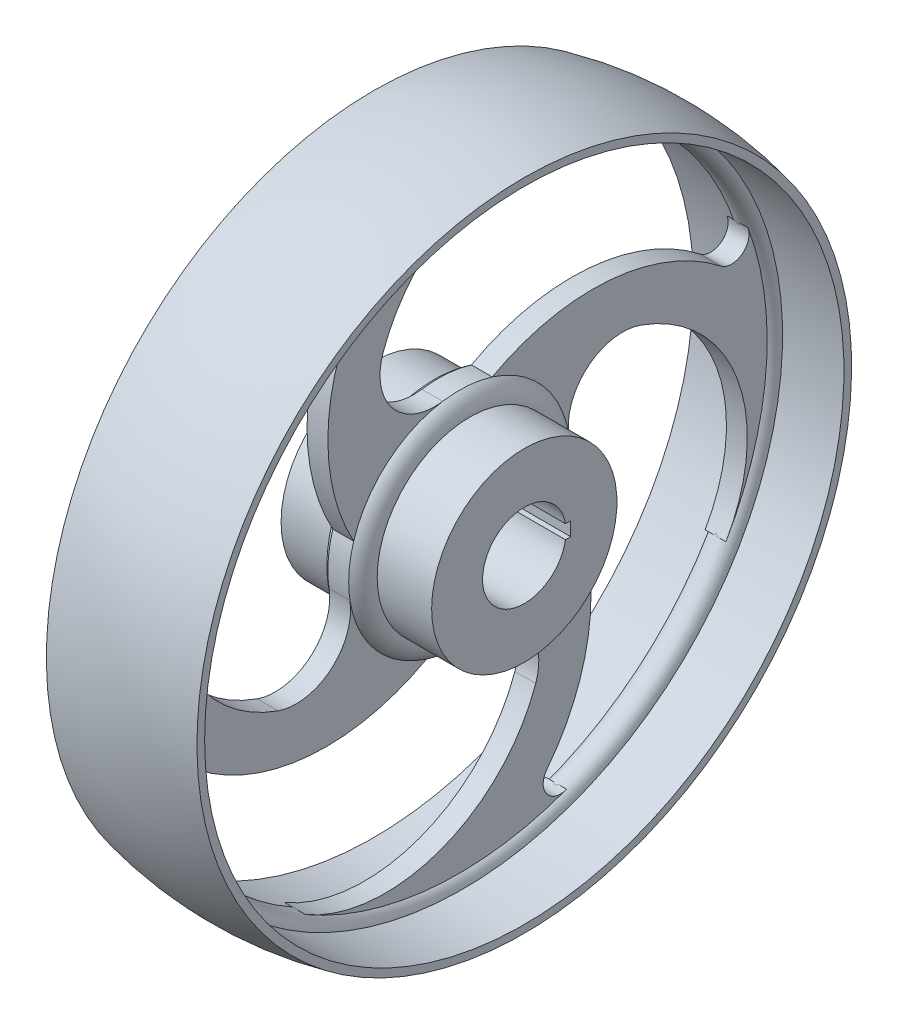
SolidWorks part; units mm, degrees
ref_plane "Front Plane" through (0, 0, 0) normal (0, 0, 1) x (1, 0, 0)
ref_plane "Top Plane" through (0, 0, 0) normal (0, 1, 0) x (1, 0, 0)
ref_plane "Right Plane" through (0, 0, 0) normal (1, 0, 0) x (0, 0, -1)
sketch "Sketch1" plane through (0, 0, 0) normal (0, 0, 1) x (1, 0, 0)
  line L0 (-32.5, 40) -> (-9, 40)
  line L1 (32.5, 18) -> (32.5, 40)
  line L2 (-32.5, 18) -> (-32.5, 40)
  line L3 (-145, 0) -> (145, 0) construction
  line L5 (-32.5, 138) -> (-32.5, 141.3108)
  line L7 (-32.5, 138) -> (-6, 138)
  line L8 (6, 138) -> (32.5, 138)
  line L9 (-145, 40) -> (145, 40) construction
  line L10 (32.5, 138) -> (32.5, 141.3108)
  line L11 (-32.5, 18) -> (32.5, 18)
  line L12 (9, 40) -> (32.5, 40)
  line L13 (-145, 18) -> (145, 18) construction
  arc A1 (32.5, 141.3108) -> (-32.5, 141.3108) centre (0, 0) ccw
  arc A3 (-6, 138) -> (6, 138) centre (0, 138.9286) ccw
  arc A6 (9, 40) -> (-9, 40) centre (0, 40) ccw
  point P3 (32.5, 0)
  point P5 (32.5, 145)
  point P6 (-32.5, 0)
  point P7 (-32.5, 145)
  point P12 (290.3079, 25.6106)
  point P13 (580.3079, 25.6106)
  point P18 (-145, 50)
  point P19 (145, 50)
  dimension "D1" = 138
  dimension "D5" = 6.0714
  dimension "D4" = 145
  dimension "D7" = 18
  dimension "D6" = 40
  dimension "D2" = 65
  dimension "D3" = 32.5
  dimension "D8" = 18
revolve "Revolve1" add sketch "Sketch1" angle 360 about L3
sketch "Sketch7" plane through (0, 0, 0) normal (1, 0, 0) x (0, 0, -1)
  circle A0 centre (0, 0) radius 132.8571
extrude "Boss-Extrude2" add sketch "Sketch7" against normal mid plane 9
sketch "Sketch8" plane through (0, 0, 0) normal (1, 0, 0) x (0, 0, -1)
  circle A0 centre (0, 0) radius 132.8571 construction
  arc A2 (14.1614, 45.648) -> (-7.213, 47.2468) centre (0, 0) ccw
  arc A4 (66.4286, 115.0577) -> (-32.9427, 78.3112) centre (32, 55.4256) ccw
  arc A5 (-32.9427, 78.3112) -> (-7.213, 47.2468) centre (-10.7622, 70.4949) ccw
  circle A6 centre (0, 0) radius 47.7942 construction
  arc A7 (112.8975, 37.7385) -> (14.1614, 45.648) centre (57.5288, -33.2143) ccw
  arc A8 (112.8975, 37.7385) -> (124.5422, 46.2629) centre (117.5116, 43.6513) ccw
  arc A9 (124.5422, 46.2629) -> (66.4286, 115.0577) centre (0, 0) ccw
  arc A10 (127.0519, 38.8437) -> (66.4286, 115.0577) centre (0, 0) ccw
  arc A11 (115.0577, -66.4286) -> (78.3112, 32.9427) centre (55.4256, -32) ccw
  arc A12 (46.2629, -124.5422) -> (115.0577, -66.4286) centre (0, 0) ccw
  arc A13 (37.7385, -112.8975) -> (46.2629, -124.5422) centre (43.6513, -117.5116) ccw
  arc A14 (37.7385, -112.8975) -> (45.648, -14.1614) centre (-33.2143, -57.5288) ccw
  arc A15 (45.648, -14.1614) -> (47.2468, 7.213) centre (0, 0) ccw
  arc A16 (78.3112, 32.9427) -> (47.2468, 7.213) centre (70.4949, 10.7622) ccw
  arc A17 (-66.4286, -115.0577) -> (32.9427, -78.3112) centre (-32, -55.4256) ccw
  arc A18 (-124.5422, -46.2629) -> (-66.4286, -115.0577) centre (0, 0) ccw
  arc A19 (-112.8975, -37.7385) -> (-124.5422, -46.2629) centre (-117.5116, -43.6513) ccw
  arc A20 (-112.8975, -37.7385) -> (-14.1614, -45.648) centre (-57.5288, 33.2143) ccw
  arc A21 (-14.1614, -45.648) -> (7.213, -47.2468) centre (0, 0) ccw
  arc A22 (32.9427, -78.3112) -> (7.213, -47.2468) centre (10.7622, -70.4949) ccw
  arc A23 (-115.0577, 66.4286) -> (-78.3112, -32.9427) centre (-55.4256, 32) ccw
  arc A24 (-46.2629, 124.5422) -> (-115.0577, 66.4286) centre (0, 0) ccw
  arc A25 (-37.7385, 112.8975) -> (-46.2629, 124.5422) centre (-43.6513, 117.5116) ccw
  arc A26 (-37.7385, 112.8975) -> (-45.648, 14.1614) centre (33.2143, 57.5288) ccw
  arc A27 (-45.648, 14.1614) -> (-47.2468, -7.213) centre (0, 0) ccw
  arc A28 (-78.3112, -32.9427) -> (-47.2468, -7.213) centre (-70.4949, -10.7622) ccw
  point P50 (0, 0)
  dimension "D1" = 4
  dimension "D4" = 180
  dimension "D5" = 15
extrude "Cut-Extrude1" cut sketch "Sketch8" against normal blind 199 and the other way blind 110 contours A9 A8 A7 A2 A5 A4 | A11 A16 A15 A14 A13 A12 | A20 A21 A22 A17 A18 A19 | A28 A27 A26 A25 A24 A23
sketch "Sketch9" plane through (32.5, 0, 0) normal (1, 0, 0) x (0, 0, -1)
  circle A0 centre (0, 0) radius 18.02
extrude "Cut-Extrude2" cut sketch "Sketch9" against normal blind 199
sketch "Sketch10" plane through (32.5, 0, 0) normal (1, 0, 0) x (0, 0, -1)
  line L1 (16.02, 3) -> (20.02, 3)
  line L2 (16.02, 3) -> (16.02, -3)
  line L3 (16.02, -3) -> (20.02, -3)
  line L4 (20.02, 3) -> (20.02, -3)
  circle A0 centre (0, 0) radius 18.02 construction
  point P0 (18.02, 0)
  point P7 (0, 0)
  point P9 (0, 0)
  dimension "D1" = 6
  dimension "D2" = 4
  dimension "D3" = 3
  dimension "D4" = 2
extrude "Cut-Extrude3" cut sketch "Sketch10" against normal blind 199
